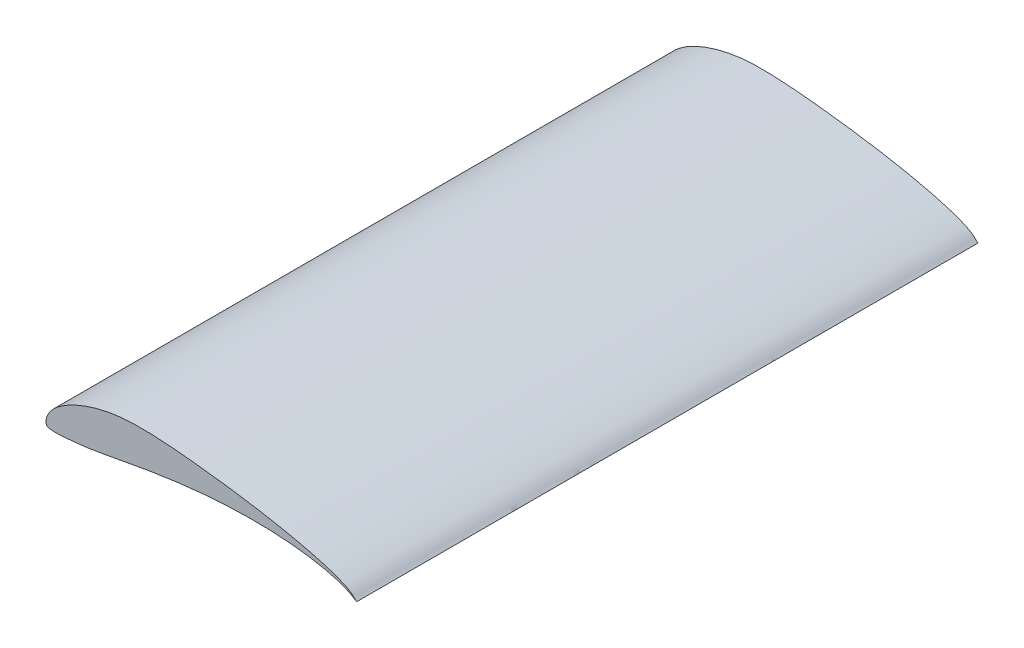
SolidWorks part; units mm, degrees
ref_plane "Front Plane" through (0, 0, 0) normal (0, 0, 1) x (1, 0, 0)
ref_plane "Top Plane" through (0, 0, 0) normal (0, 1, 0) x (1, 0, 0)
ref_plane "Right Plane" through (0, 0, 0) normal (1, 0, 0) x (0, 0, -1)
curve "Curve1"
  spline degree 3 poles (151.8102, 0.3958, 0) (152.5382, -0.0984, 0) (151.8999, 0.3772, 0) (151.4762, 0.7929, 0) (150.5354, 1.6612, 0) (149.4255, 2.5849, 0) (147.9072, 3.5162, 0) (146.0193, 4.4186, 0) (143.74, 5.3605, 0) (141.073, 6.3285, 0) (138.0307, 7.316, 0) (134.6288, 8.3144, 0) (130.8864, 9.3188, 0) (126.8242, 10.3203, 0) (122.4654, 11.3114, 0) (117.8361, 12.286, 0) (112.9645, 13.239, 0) (107.879, 14.1589, 0) (102.6118, 15.0441, 0) (97.1931, 15.8834, 0) (91.658, 16.6784, 0) (86.042, 17.4228, 0) (80.3858, 18.1141, 0) (74.7345, 18.7574, 0) (69.135, 19.3363, 0) (63.6328, 19.84, 0) (58.2667, 20.2402, 0) (53.0674, 20.5155, 0) (48.0637, 20.6344, 0) (43.2812, 20.6217, 0) (38.729, 20.3876, 0) (34.4052, 19.9131, 0) (30.2922, 19.2421, 0) (26.3891, 18.3728, 0) (22.6999, 17.3535, 0) (19.2401, 16.2022, 0) (16.0245, 14.9458, 0) (13.073, 13.591, 0) (10.3952, 12.1654, 0) (8.0055, 10.6852, 0) (5.9191, 9.1703, 0) (4.1367, 7.653, 0) (2.6842, 6.1167, 0) (1.5684, 4.5746, 0) (0.7443, 3.0743, 0) (0.2161, 1.6499, 0) (-0.0356, 0.3352, 0) (0.013, -0.7767, 0) (0.2993, -1.7966, 0) (1.3634, -2.3028, 0) (2.7941, -2.3738, 0) (4.7514, -2.4427, 0) (7.2127, -2.3365, 0) (10.1504, -2.1415, 0) (13.5317, -1.8291, 0) (17.322, -1.4063, 0) (21.5028, -0.8642, 0) (26.0721, -0.1065, 0) (31.0522, 0.8436, 0) (36.4679, 1.8776, 0) (42.2928, 2.9694, 0) (48.4902, 4.0736, 0) (55.0147, 5.1488, 0) (61.8156, 6.1591, 0) (68.8344, 7.0675, 0) (76.0079, 7.8474, 0) (83.2684, 8.4639, 0) (90.5429, 8.9009, 0) (97.7555, 9.1412, 0) (104.828, 9.1715, 0) (111.6814, 8.9899, 0) (118.2373, 8.6005, 0) (124.4169, 8.0085, 0) (130.1465, 7.2365, 0) (135.3515, 6.3069, 0) (139.971, 5.2509, 0) (143.9198, 4.1209, 0) (147.1515, 2.9148, 0) (149.4572, 1.8112, 0) (151.1572, 0.7907, 0) (151.8102, 0.3958, 0) (152.5382, -0.0984, 0) (151.8999, 0.3772, 0) knots -0.009748 -0.004147 -0.001 0 0.00098 0.003649 0.007483 0.012095 0.017526 0.024052 0.031783 0.040678 0.05071 0.061833 0.073989 0.087118 0.101145 0.115991 0.13157 0.147788 0.164551 0.181758 0.199312 0.217095 0.23499 0.252857 0.270541 0.287887 0.304773 0.321101 0.336806 0.3518 0.366031 0.379616 0.392653 0.40517 0.417172 0.428604 0.439419 0.449597 0.459102 0.467908 0.475988 0.483309 0.489875 0.495803 0.501149 0.505903 0.510047 0.513579 0.516447 0.51935 0.523823 0.529974 0.537716 0.546968 0.557637 0.56962 0.582804 0.597247 0.613135 0.630444 0.649056 0.668822 0.689595 0.71119 0.733427 0.756094 0.778989 0.80189 0.824567 0.846792 0.868338 0.888978 0.908492 0.926659 0.943286 0.958169 0.971136 0.981956 0.990252 0.995853 0.999 1 1.00098 1.003649 1.007483 periodic
sketch "Sketch1" plane through (0, 0, 0) normal (0, 0, 1) x (1, 0, 0)
  line L0 (0, 0) -> (127, 0) construction
  spline S2 degree 3 poles (126.5094, 0.3313) (127.1149, -0.0823) (126.5841, 0.3155) (126.232, 0.663) (125.4501, 1.3889) (124.5273, 2.1615) (123.2642, 2.9412) (121.693, 3.6979) (119.7957, 4.4883) (117.5754, 5.3015) (115.0423, 6.1318) (112.2095, 6.972) (109.0931, 7.8182) (105.71, 8.6626) (102.0798, 9.4991) (98.2241, 10.3225) (94.1664, 11.1285) (89.9304, 11.9074) (85.5429, 12.6578) (81.029, 13.3704) (76.418, 14.0463) (71.7394, 14.6802) (67.0271, 15.27) (62.3189, 15.8197) (57.6537, 16.3157) (53.0694, 16.7487) (48.5983, 17.0952) (44.2658, 17.3372) (40.096, 17.4483) (36.1103, 17.4493) (32.3159, 17.2652) (28.7113, 16.8801) (25.2819, 16.3309) (22.027, 15.6158) (18.9499, 14.7752) (16.0638, 13.8241) (13.3808, 12.7847) (10.9178, 11.6628) (8.6827, 10.4811) (6.6876, 9.2533) (4.9451, 7.9958) (3.456, 6.7356) (2.2417, 5.4587) (1.3082, 4.1762) (0.6177, 2.9279) (0.1741, 1.7421) (-0.0388, 0.647) (-0.001, -0.2798) (0.2351, -1.1304) (1.1207, -1.5549) (2.3129, -1.6175) (3.9439, -1.6796) (5.9955, -1.5971) (8.4442, -1.4416) (11.2629, -1.1894) (14.4227, -0.8462) (17.9084, -0.4045) (21.7183, 0.2159) (25.8709, 0.9957) (30.3869, 1.8444) (35.2439, 2.7402) (40.4115, 3.6455) (45.8516, 4.5259) (51.522, 5.3515) (57.3736, 6.0916) (63.3538, 6.7243) (69.4062, 7.2205) (75.4698, 7.5672) (81.4814, 7.75) (87.3757, 7.7583) (93.0869, 7.5904) (98.5496, 7.2501) (103.6982, 6.7418) (108.4714, 6.0846) (112.807, 5.2973) (116.6544, 4.406) (119.9426, 3.4548) (122.6329, 2.4419) (124.5519, 1.5165) (125.9662, 0.6619) (126.5094, 0.3313) (127.1149, -0.0823) (126.5841, 0.3155) knots -0.009748 -0.004147 -0.001 0 0.00098 0.003649 0.007483 0.012095 0.017526 0.024052 0.031783 0.040678 0.05071 0.061833 0.073989 0.087118 0.101145 0.115991 0.13157 0.147788 0.164551 0.181758 0.199312 0.217095 0.23499 0.252857 0.270541 0.287887 0.304773 0.321101 0.336806 0.3518 0.366031 0.379616 0.392653 0.40517 0.417172 0.428604 0.439419 0.449597 0.459102 0.467908 0.475988 0.483309 0.489875 0.495803 0.501149 0.505903 0.510047 0.513579 0.516447 0.51935 0.523823 0.529974 0.537716 0.546968 0.557637 0.56962 0.582804 0.597247 0.613135 0.630444 0.649056 0.668822 0.689595 0.71119 0.733427 0.756094 0.778989 0.80189 0.824567 0.846792 0.868338 0.888978 0.908492 0.926659 0.943286 0.958169 0.971136 0.981956 0.990252 0.995853 0.999 1 1.00098 1.003649 1.007483 only from (127, 0) to (127, 0)
  dimension "D1" = 127
extrude "Boss-Extrude1" add sketch "Sketch1" along normal blind 254
sketch "Sketch2" plane through (0, 0, 254) normal (0, 0, 1) x (1, 0, 0)
  line L0 (0, 0) -> (0, -14.4964) construction
  line L1 (0, 0) -> (152.4, 0) construction
  line L2 (152.4, 0) -> (152.4, -12.7) construction
  spline S0 degree 3 poles (151.8102, 0.3958) (152.5382, -0.0984) (151.8999, 0.3772) (151.4762, 0.7929) (150.5354, 1.6612) (149.4255, 2.5849) (147.9072, 3.5162) (146.0193, 4.4186) (143.74, 5.3605) (141.073, 6.3285) (138.0307, 7.316) (134.6288, 8.3144) (130.8864, 9.3188) (126.8242, 10.3203) (122.4654, 11.3114) (117.8361, 12.286) (112.9645, 13.239) (107.879, 14.1589) (102.6118, 15.0441) (97.1931, 15.8834) (91.658, 16.6784) (86.042, 17.4228) (80.3858, 18.1141) (74.7345, 18.7574) (69.135, 19.3363) (63.6328, 19.84) (58.2667, 20.2402) (53.0674, 20.5155) (48.0637, 20.6344) (43.2812, 20.6217) (38.729, 20.3876) (34.4052, 19.9131) (30.2922, 19.2421) (26.3891, 18.3728) (22.6999, 17.3535) (19.2401, 16.2022) (16.0245, 14.9458) (13.073, 13.591) (10.3952, 12.1654) (8.0055, 10.6852) (5.9191, 9.1703) (4.1367, 7.653) (2.6842, 6.1167) (1.5684, 4.5746) (0.7443, 3.0743) (0.2161, 1.6499) (-0.0356, 0.3352) (0.013, -0.7767) (0.2993, -1.7966) (1.3634, -2.3028) (2.7941, -2.3738) (4.7514, -2.4427) (7.2127, -2.3365) (10.1504, -2.1415) (13.5317, -1.8291) (17.322, -1.4063) (21.5028, -0.8642) (26.0721, -0.1065) (31.0522, 0.8436) (36.4679, 1.8776) (42.2928, 2.9694) (48.4902, 4.0736) (55.0147, 5.1488) (61.8156, 6.1591) (68.8344, 7.0675) (76.0079, 7.8474) (83.2684, 8.4639) (90.5429, 8.9009) (97.7555, 9.1412) (104.828, 9.1715) (111.6814, 8.9899) (118.2373, 8.6005) (124.4169, 8.0085) (130.1465, 7.2365) (135.3515, 6.3069) (139.971, 5.2509) (143.9198, 4.1209) (147.1515, 2.9148) (149.4572, 1.8112) (151.1572, 0.7907) (151.8102, 0.3958) (152.5382, -0.0984) (151.8999, 0.3772) knots -0.009748 -0.004147 -0.001 0 0.00098 0.003649 0.007483 0.012095 0.017526 0.024052 0.031783 0.040678 0.05071 0.061833 0.073989 0.087118 0.101145 0.115991 0.13157 0.147788 0.164551 0.181758 0.199312 0.217095 0.23499 0.252857 0.270541 0.287887 0.304773 0.321101 0.336806 0.3518 0.366031 0.379616 0.392653 0.40517 0.417172 0.428604 0.439419 0.449597 0.459102 0.467908 0.475988 0.483309 0.489875 0.495803 0.501149 0.505903 0.510047 0.513579 0.516447 0.51935 0.523823 0.529974 0.537716 0.546968 0.557637 0.56962 0.582804 0.597247 0.613135 0.630444 0.649056 0.668822 0.689595 0.71119 0.733427 0.756094 0.778989 0.80189 0.824567 0.846792 0.868338 0.888978 0.908492 0.926659 0.943286 0.958169 0.971136 0.981956 0.990252 0.995853 0.999 1 1.00098 1.003649 1.007483 only from (152.4, 0) to (152.4, 0) construction
sketch "Sketch3" plane through (0, 0, 0) normal (0, 0, -1) x (-1, 0, 0)
  line L0 (0, -14.4964) -> (0, 0) construction
  line L1 (0, 0) -> (-152.4, 0) construction
  line L2 (-152.4, 0) -> (-152.4, -12.7) construction
sketch "Sketch4" plane through (0, 0, 0) normal (0, 0, -1) x (-1, 0, 0)
  spline S1 degree 3 poles (-126.5841, 0.3155) (-127.1149, -0.0823) (-126.5094, 0.3313) (-125.9662, 0.6619) (-124.5519, 1.5165) (-122.6329, 2.4419) (-119.9426, 3.4548) (-116.6544, 4.406) (-112.807, 5.2973) (-108.4714, 6.0846) (-103.6982, 6.7418) (-98.5496, 7.2501) (-93.0869, 7.5904) (-87.3757, 7.7583) (-81.4814, 7.75) (-75.4698, 7.5672) (-69.4062, 7.2205) (-63.3538, 6.7243) (-57.3736, 6.0916) (-51.522, 5.3515) (-45.8516, 4.5259) (-40.4115, 3.6455) (-35.2439, 2.7402) (-30.3869, 1.8444) (-25.8709, 0.9957) (-21.7183, 0.2159) (-17.9084, -0.4045) (-14.4227, -0.8462) (-11.2629, -1.1894) (-8.4442, -1.4416) (-5.9955, -1.5971) (-3.9439, -1.6796) (-2.3129, -1.6175) (-1.1207, -1.5549) (-0.2351, -1.1304) (0.001, -0.2798) (0.0388, 0.647) (-0.1741, 1.7421) (-0.6177, 2.9279) (-1.3082, 4.1762) (-2.2417, 5.4587) (-3.456, 6.7356) (-4.9451, 7.9958) (-6.6876, 9.2533) (-8.6827, 10.4811) (-10.9178, 11.6628) (-13.3808, 12.7847) (-16.0638, 13.8241) (-18.9499, 14.7752) (-22.027, 15.6158) (-25.2819, 16.3309) (-28.7113, 16.8801) (-32.3159, 17.2652) (-36.1103, 17.4493) (-40.096, 17.4483) (-44.2658, 17.3372) (-48.5983, 17.0952) (-53.0694, 16.7487) (-57.6537, 16.3157) (-62.3189, 15.8197) (-67.0271, 15.27) (-71.7394, 14.6802) (-76.418, 14.0463) (-81.029, 13.3704) (-85.5429, 12.6578) (-89.9304, 11.9074) (-94.1664, 11.1285) (-98.2241, 10.3225) (-102.0798, 9.4991) (-105.71, 8.6626) (-109.0931, 7.8182) (-112.2095, 6.972) (-115.0423, 6.1318) (-117.5754, 5.3015) (-119.7957, 4.4883) (-121.693, 3.6979) (-123.2642, 2.9412) (-124.5273, 2.1615) (-125.4501, 1.3889) (-126.232, 0.663) (-126.5841, 0.3155) (-127.1149, -0.0823) (-126.5094, 0.3313) knots -0.007483 -0.003649 -0.00098 0 0.001 0.004147 0.009748 0.018044 0.028864 0.041831 0.056714 0.073341 0.091508 0.111022 0.131662 0.153208 0.175433 0.19811 0.221011 0.243906 0.266573 0.28881 0.310405 0.331178 0.350944 0.369556 0.386865 0.402753 0.417196 0.43038 0.442363 0.453032 0.462284 0.470026 0.476177 0.48065 0.483553 0.486421 0.489953 0.494097 0.498851 0.504197 0.510125 0.516691 0.524012 0.532092 0.540898 0.550403 0.560581 0.571396 0.582828 0.59483 0.607347 0.620384 0.633969 0.6482 0.663194 0.678899 0.695227 0.712113 0.729459 0.747143 0.76501 0.782905 0.800688 0.818242 0.835449 0.852212 0.86843 0.884009 0.898855 0.912882 0.926011 0.938167 0.94929 0.959322 0.968217 0.975948 0.982474 0.987905 0.992517 0.996351 0.99902 1 1.001 1.004147 1.009748 only from (-127, 0) to (-127, 0)
  spline S2 degree 3 poles (-126.5841, 0.3155) (-127.1149, -0.0823) (-126.5094, 0.3313) (-125.9662, 0.6619) (-124.5519, 1.5165) (-122.6329, 2.4419) (-119.9426, 3.4548) (-116.6544, 4.406) (-112.807, 5.2973) (-108.4714, 6.0846) (-103.6982, 6.7418) (-98.5496, 7.2501) (-93.0869, 7.5904) (-87.3757, 7.7583) (-81.4814, 7.75) (-75.4698, 7.5672) (-69.4062, 7.2205) (-63.3538, 6.7243) (-57.3736, 6.0916) (-51.522, 5.3515) (-45.8516, 4.5259) (-40.4115, 3.6455) (-35.2439, 2.7402) (-30.3869, 1.8444) (-25.8709, 0.9957) (-21.7183, 0.2159) (-17.9084, -0.4045) (-14.4227, -0.8462) (-11.2629, -1.1894) (-8.4442, -1.4416) (-5.9955, -1.5971) (-3.9439, -1.6796) (-2.3129, -1.6175) (-1.1207, -1.5549) (-0.2351, -1.1304) (0.001, -0.2798) (0.0388, 0.647) (-0.1741, 1.7421) (-0.6177, 2.9279) (-1.3082, 4.1762) (-2.2417, 5.4587) (-3.456, 6.7356) (-4.9451, 7.9958) (-6.6876, 9.2533) (-8.6827, 10.4811) (-10.9178, 11.6628) (-13.3808, 12.7847) (-16.0638, 13.8241) (-18.9499, 14.7752) (-22.027, 15.6158) (-25.2819, 16.3309) (-28.7113, 16.8801) (-32.3159, 17.2652) (-36.1103, 17.4493) (-40.096, 17.4483) (-44.2658, 17.3372) (-48.5983, 17.0952) (-53.0694, 16.7487) (-57.6537, 16.3157) (-62.3189, 15.8197) (-67.0271, 15.27) (-71.7394, 14.6802) (-76.418, 14.0463) (-81.029, 13.3704) (-85.5429, 12.6578) (-89.9304, 11.9074) (-94.1664, 11.1285) (-98.2241, 10.3225) (-102.0798, 9.4991) (-105.71, 8.6626) (-109.0931, 7.8182) (-112.2095, 6.972) (-115.0423, 6.1318) (-117.5754, 5.3015) (-119.7957, 4.4883) (-121.693, 3.6979) (-123.2642, 2.9412) (-124.5273, 2.1615) (-125.4501, 1.3889) (-126.232, 0.663) (-126.5841, 0.3155) (-127.1149, -0.0823) (-126.5094, 0.3313) knots -0.007483 -0.003649 -0.00098 0 0.001 0.004147 0.009748 0.018044 0.028864 0.041831 0.056714 0.073341 0.091508 0.111022 0.131662 0.153208 0.175433 0.19811 0.221011 0.243906 0.266573 0.28881 0.310405 0.331178 0.350944 0.369556 0.386865 0.402753 0.417196 0.43038 0.442363 0.453032 0.462284 0.470026 0.476177 0.48065 0.483553 0.486421 0.489953 0.494097 0.498851 0.504197 0.510125 0.516691 0.524012 0.532092 0.540898 0.550403 0.560581 0.571396 0.582828 0.59483 0.607347 0.620384 0.633969 0.6482 0.663194 0.678899 0.695227 0.712113 0.729459 0.747143 0.76501 0.782905 0.800688 0.818242 0.835449 0.852212 0.86843 0.884009 0.898855 0.912882 0.926011 0.938167 0.94929 0.959322 0.968217 0.975948 0.982474 0.987905 0.992517 0.996351 0.99902 1 1.001 1.004147 1.009748 only from (-127, 0) to (-127, 0)
  dimension "D1" = 0
sketch3d "3DSketch1"
  line L0 (0, 0, 254) -> (0, 0, 0) construction
